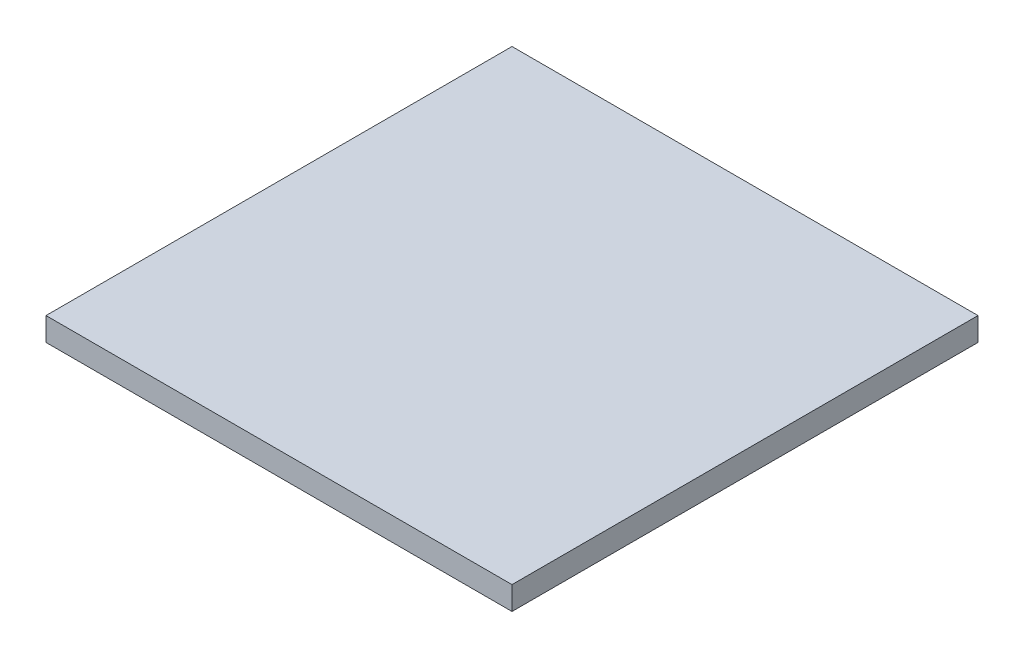
SolidWorks part; units mm, degrees
ref_plane "Front Plane" through (0, 0, 0) normal (0, 0, 1) x (1, 0, 0)
ref_plane "Top Plane" through (0, 0, 0) normal (0, 1, 0) x (1, 0, 0)
ref_plane "Right Plane" through (0, 0, 0) normal (1, 0, 0) x (0, 0, -1)
sketch "Sketch2" plane through (0, 0, 0) normal (0, 1, 0) x (1, 0, 0)
  line L1 (-10000, 10000) -> (10000, 10000)
  line L2 (-10000, 10000) -> (-10000, -10000)
  line L3 (-10000, -10000) -> (10000, -10000)
  line L4 (10000, 10000) -> (10000, -10000)
  line L5 (-10000, 10000) -> (10000, -10000) construction
  line L6 (-10000, -10000) -> (10000, 10000) construction
  point P0 (0, 0)
  dimension "D1" = 20000
  dimension "D2" = 20000
extrude "Boss-Extrude1" add sketch "Sketch2" against normal blind 1000
